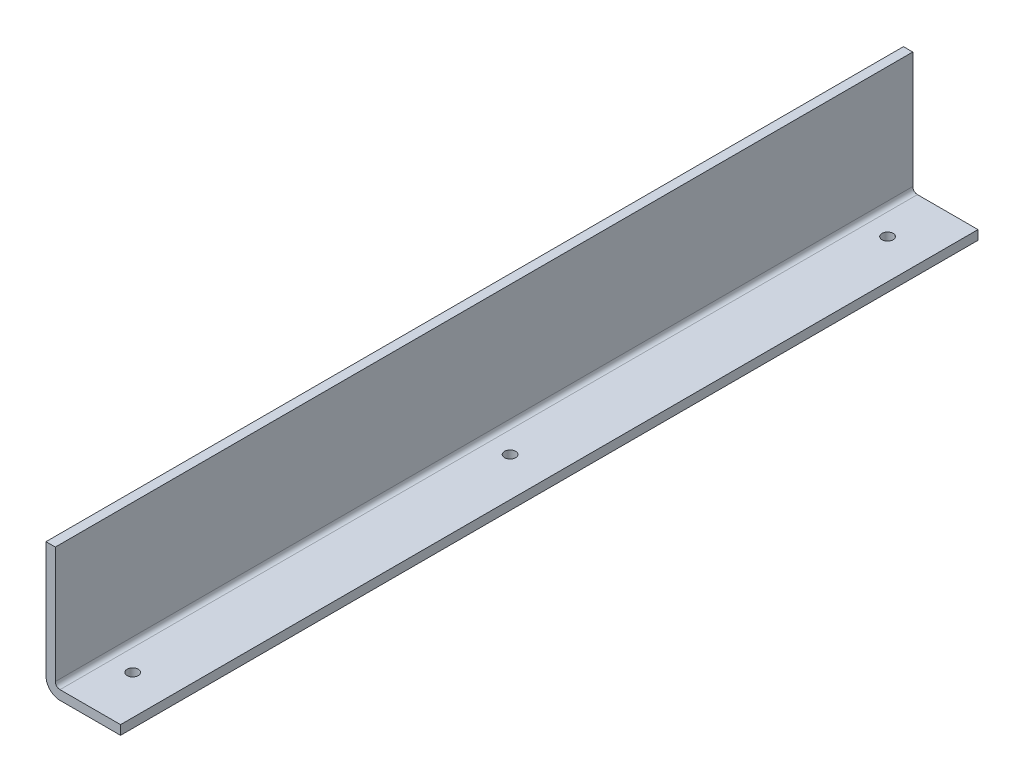
SolidWorks part; units mm, degrees
material "3.0205 (EN-AW 1200)"
ref_plane "前视基准面" through (0, 0, 0) normal (0, 0, 1) x (1, 0, 0)
ref_plane "上视基准面" through (0, 0, 0) normal (0, 1, 0) x (1, 0, 0)
ref_plane "右视基准面" through (0, 0, 0) normal (1, 0, 0) x (0, 0, -1)
sketch "草图1" plane through (0, 0, 0) normal (0, 0, 1) x (1, 0, 0)
  line L0 (0, 140) -> (0, 15)
  line L1 (15, 0) -> (80, 0)
  line L2 (10, 140) -> (10, 15)
  line L3 (15, 10) -> (80, 10)
  line L4 (0, 140) -> (10, 140)
  line L5 (80, 10) -> (80, 0)
  arc A0 (0, 15) -> (15, 0) centre (15, 15) ccw
  arc A1 (10, 15) -> (15, 10) centre (15, 15) ccw
  point P6 (0, 0)
  dimension "D3" = 15
  dimension "D1" = 140
  dimension "D2" = 80
  dimension "D4" = 10
extrude "凸台-拉伸1" add sketch "草图1" along normal mid plane 920
sketch "草图2" plane through (0, 0, 0) normal (0, 0, 1) x (1, 0, 0)
  line L0 (38, 38.7283) -> (38, -17.0396) construction
  line L1 (38, 10) -> (44, 10)
  line L2 (80, 10) -> (15, 10) construction
  line L3 (44, 10) -> (44, 0)
  line L4 (15, 0) -> (80, 0) construction
  line L5 (44, 0) -> (38, 0)
  line L6 (0, 140) -> (0, 15) construction
  line L7 (38, 10) -> (38, 0)
  dimension "D1" = 6
  dimension "D2" = 38
revolve "切除-旋转1" cut sketch "草图2" angle 360 about L0
pattern_linear "阵列(线性)1" count 2 spacing 405 along (0, 0, 1) count 2 spacing 405 along (0, 0, -1) of "切除-旋转1"
